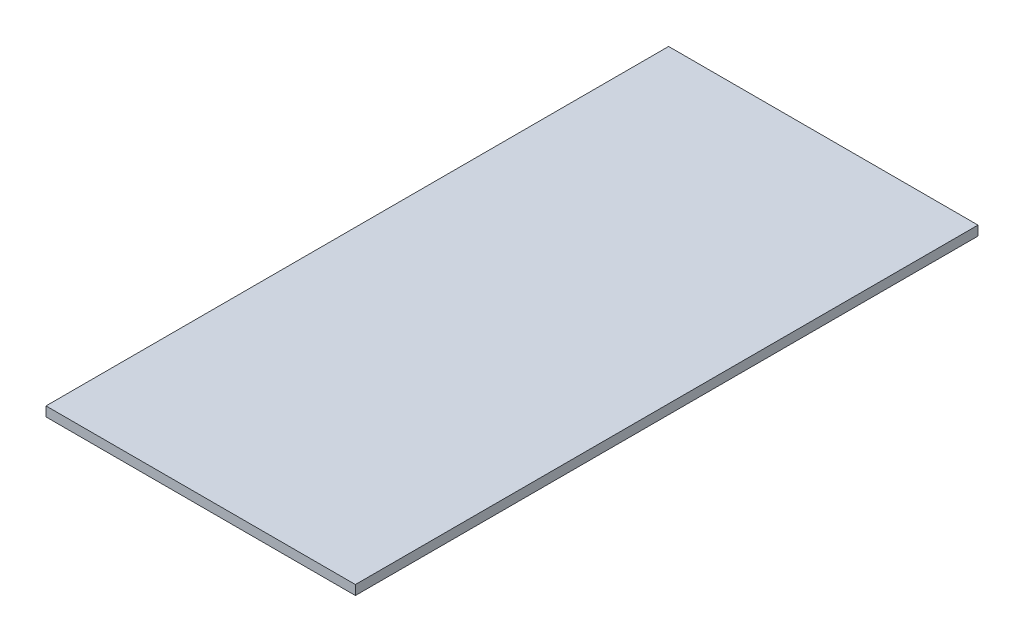
SolidWorks part; units mm, degrees
ref_plane "Front" through (0, 0, 0) normal (0, 0, 1) x (1, 0, 0)
ref_plane "Top" through (0, 0, 0) normal (0, 1, 0) x (1, 0, 0)
ref_plane "Right" through (0, 0, 0) normal (1, 0, 0) x (0, 0, -1)
sketch "Sketch1" plane through (0, 0, 0) normal (0, 1, 0) x (1, 0, 0)
  line L1 (0, 0) -> (102.87, 0)
  line L2 (0, 0) -> (0, 207.01)
  line L3 (0, 207.01) -> (102.87, 207.01)
  line L4 (102.87, 0) -> (102.87, 207.01)
  dimension "D1" = 207.01
  dimension "D2" = 102.87
extrude "Boss-Extrude1" add sketch "Sketch1" along normal blind 3.175
